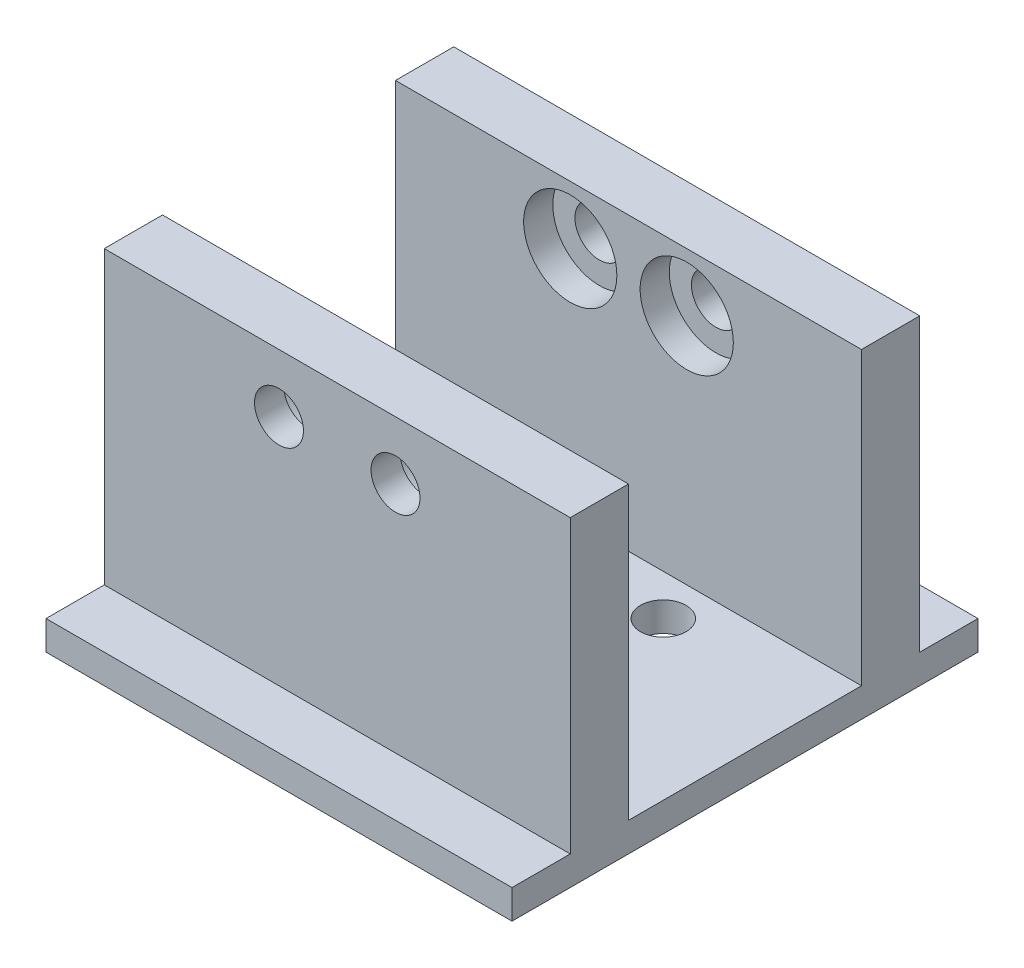
SolidWorks part; units mm, degrees
material "PVC Rigid"
ref_plane "Front Plane" through (0, 0, 0) normal (0, 0, 1) x (1, 0, 0)
ref_plane "Top Plane" through (0, 0, 0) normal (0, 1, 0) x (1, 0, 0)
ref_plane "Right Plane" through (0, 0, 0) normal (1, 0, 0) x (0, 0, -1)
sketch "Sketch1" plane through (0, 0, 0) normal (0, 1, 0) x (1, 0, 0)
  line L1 (-25.4, 25.4) -> (25.4, 25.4)
  line L2 (-25.4, 25.4) -> (-25.4, -25.4)
  line L3 (-25.4, -25.4) -> (25.4, -25.4)
  line L4 (25.4, 25.4) -> (25.4, -25.4)
  line L5 (-25.4, 25.4) -> (25.4, -25.4) construction
  line L6 (-25.4, -25.4) -> (25.4, 25.4) construction
  circle A0 centre (-8.2439, 8.2439) radius 2.4892
  circle A1 centre (8.2439, 8.2439) radius 2.4892
  circle A2 centre (8.2439, -8.2439) radius 2.4892
  circle A3 centre (-8.2439, -8.2439) radius 2.4892
  circle A4 centre (0, 0) radius 7.62
  point P0 (0, 0)
  dimension "D2" = 4.9784
  dimension "D4" = 15.24
  dimension "D1" = 25.4
  dimension "D3" = 11.6586
extrude "Boss-Extrude1" add sketch "Sketch1" along normal blind 3.175
sketch "Sketch2" plane through (0, 3.175, 0) normal (0, 1, 0) x (1, 0, 0)
  line L0 (25.4, -25.4) -> (25.4, 25.4) construction
  line L1 (-25.4, 19.05) -> (25.4, 19.05)
  line L2 (-25.4, 19.05) -> (-25.4, 12.7)
  line L3 (-25.4, 12.7) -> (25.4, 12.7)
  line L4 (25.4, 19.05) -> (25.4, 12.7)
  line L5 (-25.4, 19.05) -> (25.4, 12.7) construction
  line L6 (-25.4, 12.7) -> (25.4, 19.05) construction
  line L7 (-25.4, 25.4) -> (-25.4, -25.4) construction
  line L9 (-25.4, -12.7) -> (25.4, -12.7)
  line L10 (-25.4, -12.7) -> (-25.4, -19.05)
  line L11 (-25.4, -19.05) -> (25.4, -19.05)
  line L12 (25.4, -12.7) -> (25.4, -19.05)
  line L13 (-25.4, -12.7) -> (25.4, -19.05) construction
  line L14 (-25.4, -19.05) -> (25.4, -12.7) construction
  point P0 (0, 15.875)
  point P11 (0, -15.875)
  dimension "D1" = 6.35
  dimension "D2" = 15.875
  dimension "D3" = 15.875
extrude "Boss-Extrude2" add sketch "Sketch2" along normal blind 31.75
sketch "Sketch3" plane through (0, 0, -19.05) normal (0, 0, -1) x (-1, 0, 0)
  line L0 (-6.35, 28.575) -> (0, 28.575) construction
  line L1 (0, 28.575) -> (6.35, 28.575) construction
  line L2 (-25.4, 34.925) -> (25.4, 34.925) construction
  circle A0 centre (-6.35, 28.575) radius 2.667
  circle A1 centre (6.35, 28.575) radius 2.667
  dimension "D1" = 5.334
  dimension "D2" = 6.35
  dimension "D3" = 6.35
  dimension "D4" = 6.35
extrude "Cut-Extrude1" cut sketch "Sketch3" against normal up to surface (38.1 mm away) up to face at (0, 19.05, 19.05)
sketch "Sketch5" plane through (0, 0, -12.7) normal (0, 0, 1) x (1, 0, 0)
  circle A0 centre (-6.35, 28.575) radius 5.08
  circle A1 centre (6.35, 28.575) radius 5.08
  dimension "D1" = 10.16
extrude "Cut-Extrude2" cut sketch "Sketch5" against normal blind 3.175
sketch "Sketch6" plane through (0, 0, 12.7) normal (0, 0, -1) x (-1, 0, 0)
  circle A0 centre (-6.35, 28.575) radius 5.08
  circle A1 centre (6.35, 28.575) radius 5.08
  dimension "D1" = 10.16
extrude "Cut-Extrude3" cut sketch "Sketch6" against normal blind 3.175
